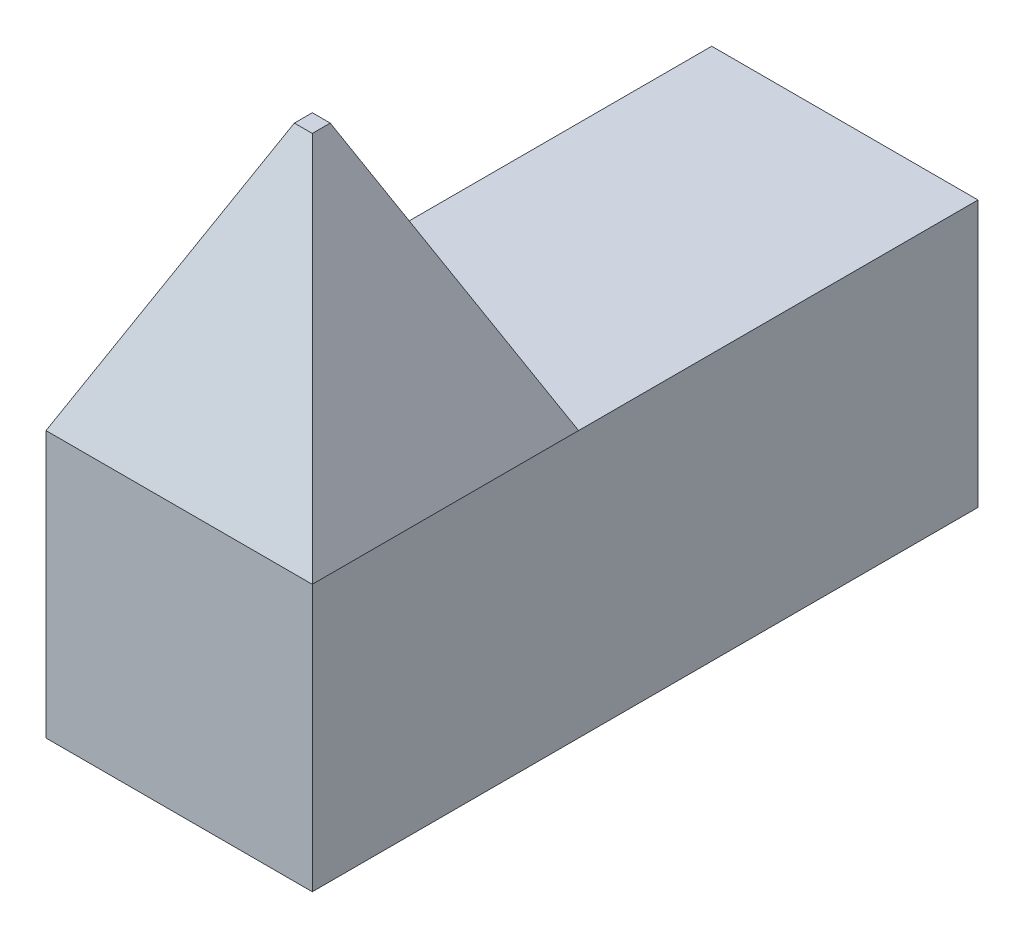
SolidWorks part; units mm, degrees
ref_plane "Front Plane" through (0, 0, 0) normal (0, 0, 1) x (1, 0, 0)
ref_plane "Top Plane" through (0, 0, 0) normal (0, 1, 0) x (1, 0, 0)
ref_plane "Right Plane" through (0, 0, 0) normal (1, 0, 0) x (0, 0, -1)
sketch "Sketch1" plane through (0, 0, 0) normal (0, 0, 1) x (1, 0, 0)
  line L1 (0, 0) -> (40, 0)
  line L2 (0, 0) -> (0, 40)
  line L3 (0, 40) -> (40, 40)
  line L4 (40, 0) -> (40, 40)
  dimension "D1" = 40
extrude "Boss-Extrude1" add sketch "Sketch1" along normal blind 100
sketch "Sketch2" plane through (0, 40, 0) normal (0, 1, 0) x (1, 0, 0)
  line L0 (0, -60) -> (40, -60)
  line L1 (0, -100) -> (0, 0) construction
  line L2 (40, -100) -> (40, 0) construction
  line L3 (20, -60) -> (20, -100) construction
  line L4 (40, -100) -> (0, -100) construction
  line L5 (40, 0) -> (0, 0) construction
  line L6 (0, -60) -> (0, -100)
  line L7 (0, -100) -> (40, -100)
  line L8 (40, -100) -> (40, -60)
extrude "Boss-Extrude2" add sketch "Sketch2" along normal blind 40 draft 25
